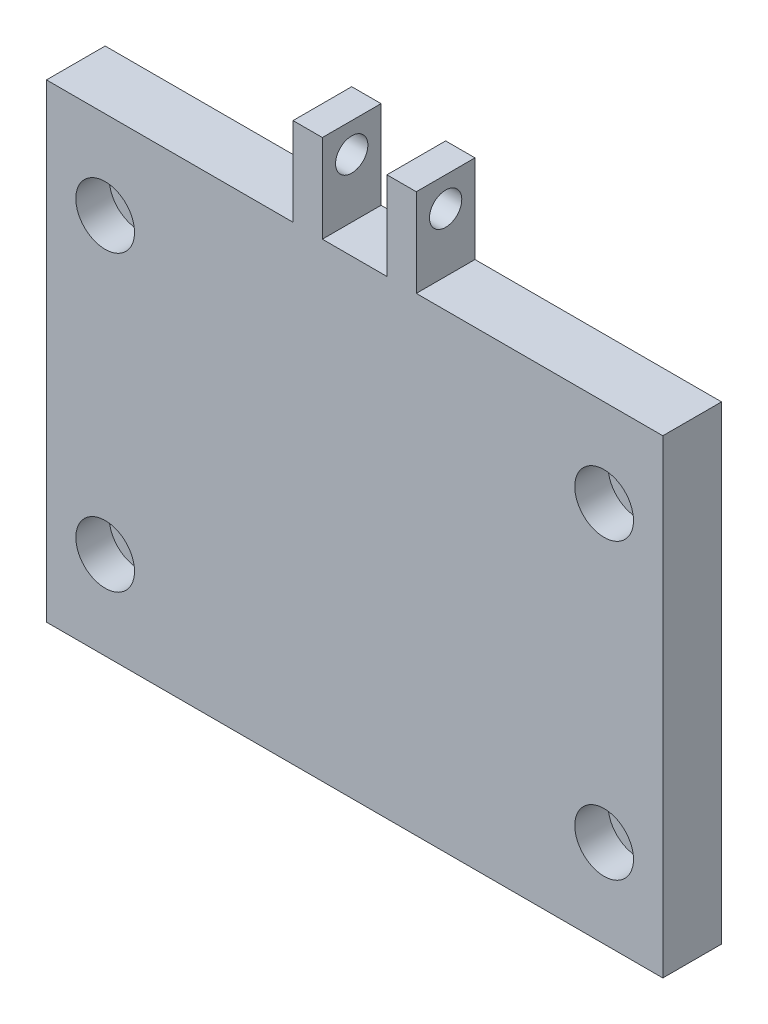
SolidWorks part; units mm, degrees
material "A6061"
ref_plane "前视基准面" through (0, 0, 0) normal (0, 0, 1) x (1, 0, 0)
ref_plane "上视基准面" through (0, 0, 0) normal (0, 1, 0) x (1, 0, 0)
ref_plane "右视基准面" through (0, 0, 0) normal (1, 0, 0) x (0, 0, -1)
sketch "草图1" plane through (0, 0, 0) normal (0, 0, 1) x (1, 0, 0)
  line L0 (0, 46.9964) -> (0, -60.1981) construction
  line L1 (52.5, 40) -> (-52.5, 40)
  line L2 (52.5, 40) -> (52.5, -40)
  line L3 (52.5, -40) -> (-52.5, -40)
  line L4 (-52.5, 40) -> (-52.5, -40)
  line L5 (52.5, 40) -> (-52.5, -40) construction
  line L6 (52.5, -40) -> (-52.5, 40) construction
  line L7 (-72.2657, 0) -> (73.0151, 0) construction
  line L8 (-10.5, 40) -> (-10.5, 55)
  line L9 (-10.5, 55) -> (-5.5, 55)
  line L10 (-5.5, 55) -> (-5.5, 40)
  line L11 (5.5, 55) -> (5.5, 40)
  line L12 (10.5, 55) -> (5.5, 55)
  line L13 (10.5, 40) -> (10.5, 55)
  circle A0 centre (-42.5, 25) radius 2.5
  circle A1 centre (42.5, 25) radius 2.5
  circle A2 centre (42.5, -25) radius 2.5
  circle A3 centre (-42.5, -25) radius 2.5
  point P0 (0, 0)
  dimension "D1" = 5
  dimension "D2" = 50
  dimension "D3" = 85
  dimension "D4" = 80
  dimension "D5" = 105
  dimension "D6" = 11
  dimension "D7" = 5
  dimension "D8" = 15
extrude "凸台-拉伸1" add sketch "草图1" along normal mid plane 10 contours L1 L4 L3 L2 A1 A0 A2 A3 | L10 L9 L8 L1 | L1 L13 L12 L11
hole_wizard "打孔尺寸(%根据)内六角圆柱头螺钉的类型1" positions "草图2" profile "草图3" counterbore size "M5" standard "GB" end condition through all
sketch "草图2" plane through (0, 0, 5) normal (0, 0, 1) x (1, 0, 0)
  point P0 (-42.5, 25)
  point P3 (42.5, 25)
  point P6 (42.5, -25)
  point P9 (-42.5, -25)
sketch "草图3" plane through (-42.5, 25, 5) normal (1, 0, 0) x (0, -1, 0)
  line L0 (0, 0) -> (0, 10)
  line L1 (0, 10) -> (2.75, 10)
  line L3 (2.75, 10) -> (2.75, 5.7)
  line L4 (2.75, 5.7) -> (5, 5.7)
  line L5 (5, 5.7) -> (5, 0)
  line L7 (5, 0) -> (0, 0)
  line L11 (0, -6.35) -> (0, 107.95) construction
  dimension "通孔孔直径" = 5.5
  dimension "通孔孔深度" = 10
  dimension "柱形沉头孔直径" = 10
  dimension "柱形沉头孔深度" = 5.7
sketch "草图4" plane through (-10.5, 0, 0) normal (-1, 0, 0) x (0, 0, 1)
  line L0 (5, 40) -> (-5, 40) construction
  line L1 (0, -2.3206) -> (0, 58.5338) construction
  circle A0 centre (0, 50) radius 2.75
  dimension "D1" = 5.5
  dimension "D2" = 10
extrude "切除-拉伸1" cut sketch "草图4" against normal through all
